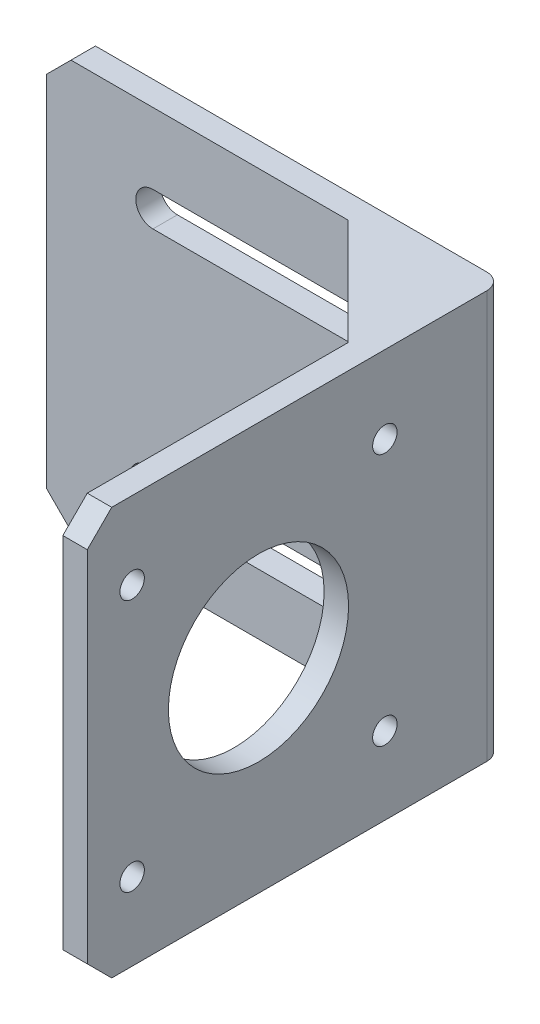
SolidWorks part; units mm, degrees
ref_plane "Płaszczyzna przednia" through (0, 0, 0) normal (0, 0, 1) x (1, 0, 0)
ref_plane "Płaszczyzna górna" through (0, 0, 0) normal (0, 1, 0) x (1, 0, 0)
ref_plane "Płaszczyzna prawa" through (0, 0, 0) normal (1, 0, 0) x (0, 0, -1)
sketch "Szkic5" plane through (0, 0, 0) normal (0, 0, 1) x (1, 0, 0)
  line L1 (-26.5, -25) -> (26.5, -25)
  line L2 (-26.5, -25) -> (-26.5, 25)
  line L3 (-26.5, 25) -> (26.5, 25)
  line L4 (26.5, -25) -> (26.5, 25)
  line L5 (-26.5, -25) -> (26.5, 25) construction
  line L6 (-26.5, 25) -> (26.5, -25) construction
  point P0 (0, 0)
  dimension "D1" = 53
  dimension "D2" = 50
extrude "Dodanie-wyciągnięcie2" add sketch "Szkic5" along normal blind 3
sketch "Szkic6" plane through (0, 0, 3) normal (0, 0, 1) x (1, 0, 0)
  line L0 (26.5, 25) -> (-26.5, 25) construction
  line L1 (26.5, -25) -> (23.5, -25)
  line L2 (26.5, -25) -> (26.5, 25)
  line L3 (26.5, 25) -> (23.5, 25)
  line L4 (23.5, -25) -> (23.5, 25)
  dimension "D1" = 3
extrude "Dodanie-wyciągnięcie3" add sketch "Szkic6" along normal blind 48
fillet "Zaokrąglenie1" radius 2 1 edges at (26.5, 0, 0)
sketch "Szkic7" plane through (26.5, 0, 0) normal (1, 0, 0) x (0, 0, -1)
  circle A0 centre (-30, 0) radius 11.05
chamfer "Sfazowanie2" distance 3 angle 45 3 edges at (-26.5, -25, 1.5) (-26.5, 25, 1.5) (25, -25, 51)
chamfer "Sfazowanie4" distance 3 angle 45 1 edges at (25, 25, 51)
extrude "Wytnij-wyciągnięcie2" cut sketch "Szkic7" against normal up to next
sketch "Szkic9" plane through (26.5, 0, 0) normal (1, 0, 0) x (0, 0, -1)
  circle A0 centre (-45.5, 15.5) radius 1.5
extrude "Wytnij-wyciągnięcie3" cut sketch "Szkic9" against normal up to next
sketch "Szkic10" plane through (26.5, 0, 0) normal (1, 0, 0) x (0, 0, -1)
  circle A0 centre (-45.5, -15.5) radius 1.5
extrude "Wytnij-wyciągnięcie4" cut sketch "Szkic10" against normal up to next
sketch "Szkic11" plane through (26.5, 0, 0) normal (1, 0, 0) x (0, 0, -1)
  circle A0 centre (-14.5, -15.5) radius 1.5
extrude "Wytnij-wyciągnięcie5" cut sketch "Szkic11" against normal up to next
sketch "Szkic12" plane through (26.5, 0, 0) normal (1, 0, 0) x (0, 0, -1)
  circle A0 centre (-14.5, 15.5) radius 1.5
extrude "Wytnij-wyciągnięcie6" cut sketch "Szkic12" against normal up to next
sketch "Szkic15" plane through (0, 25, 0) normal (0, 1, 0) x (1, 0, 0)
  line L0 (23.5, -16) -> (10.5, -3)
  line L1 (23.5, -48) -> (23.5, -3) construction
  line L2 (23.5, -3) -> (-23.5, -3) construction
  line L3 (10.5, -3) -> (23.5, -3)
  line L4 (23.5, -3) -> (23.5, -16)
  dimension "D1" = 13
  dimension "D2" = 13
extrude "Dodanie-wyciągnięcie4" add sketch "Szkic15" against normal blind 3
sketch "Szkic16" plane through (0, -25, 0) normal (0, -1, 0) x (1, 0, 0)
  line L0 (23.5, 3) -> (23.5, 16)
  line L1 (23.5, 48) -> (23.5, 3) construction
  line L2 (23.5, 16) -> (10.5, 3)
  line L3 (-23.5, 3) -> (23.5, 3) construction
  line L4 (10.5, 3) -> (23.5, 3)
  dimension "D1" = 13
  dimension "D2" = 13
extrude "Dodanie-wyciągnięcie5" add sketch "Szkic16" against normal blind 3
sketch "Szkic17" plane through (0, 0, 3) normal (0, 0, 1) x (1, 0, 0)
  line L0 (16.5518, 14.1938) -> (-13.4482, 14.1938) construction
  line L1 (16.5518, 12.0938) -> (-13.4482, 12.0938)
  line L2 (16.5518, 16.2938) -> (-13.4482, 16.2938)
  line L3 (15.8289, -15.4772) -> (-14.1711, -15.4772) construction
  line L4 (15.8289, -17.5772) -> (-14.1711, -17.5772)
  line L5 (15.8289, -13.3772) -> (-14.1711, -13.3772)
  arc A0 (16.5518, 12.0938) -> (16.5518, 16.2938) centre (16.5518, 14.1938) ccw
  arc A1 (-13.4482, 16.2938) -> (-13.4482, 12.0938) centre (-13.4482, 14.1938) ccw
  arc A2 (15.8289, -17.5772) -> (15.8289, -13.3772) centre (15.8289, -15.4772) ccw
  arc A3 (-14.1711, -13.3772) -> (-14.1711, -17.5772) centre (-14.1711, -15.4772) ccw
  point P2 (1.5518, 14.1938)
  point P7 (0.8289, -15.4772)
extrude "Wytnij-wyciągnięcie7" cut sketch "Szkic17" against normal blind 3
